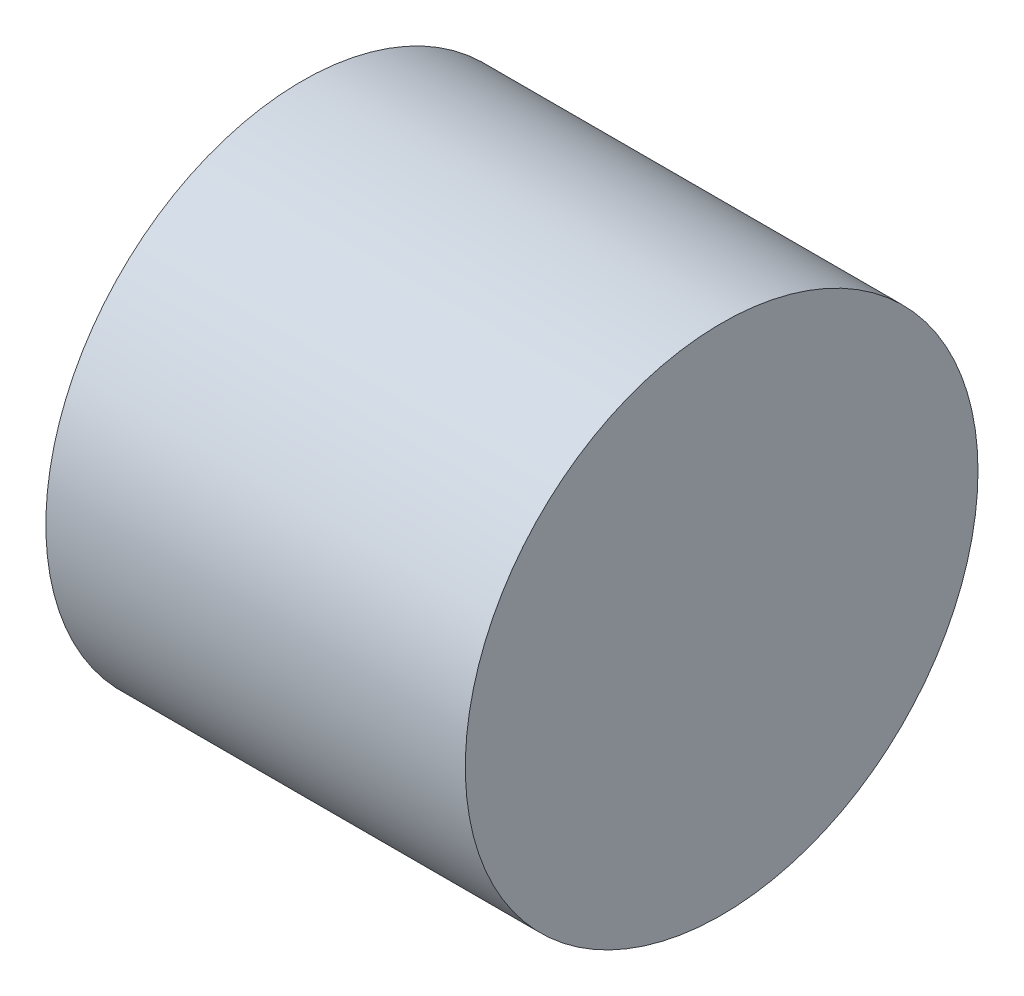
SolidWorks part; units mm, degrees
ref_plane "前视基准面" through (0, 0, 0) normal (0, 0, 1) x (1, 0, 0)
ref_plane "上视基准面" through (0, 0, 0) normal (0, 1, 0) x (1, 0, 0)
ref_plane "右视基准面" through (0, 0, 0) normal (1, 0, 0) x (0, 0, -1)
other "Configuration Table"
sketch "草图1" plane through (0, 0, 0) normal (1, 0, 0) x (0, 0, -1)
  circle A0 centre (0, 0) radius 275
  dimension "D1" = 550
extrude "凸台-拉伸1" add sketch "草图1" along normal blind 450
